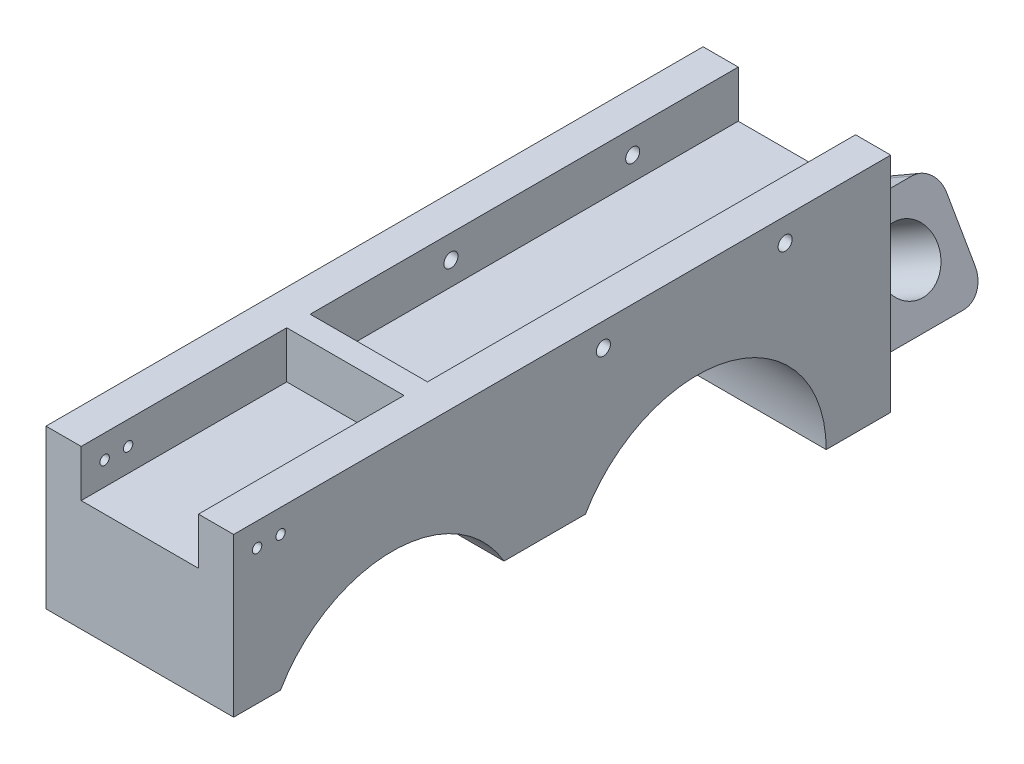
SolidWorks part; units mm, degrees
ref_plane "Спереди" through (0, 0, 0) normal (0, 0, 1) x (1, 0, 0)
ref_plane "Сверху" through (0, 0, 0) normal (0, 1, 0) x (1, 0, 0)
ref_plane "Справа" through (0, 0, 0) normal (1, 0, 0) x (0, 0, -1)
sketch "Эскиз1" plane through (0, 0, 0) normal (1, 0, 0) x (0, 0, -1)
  line L5 (0, 0) -> (0, -95)
  line L23 (-82.5, -95) -> (-130.1314, -67.5) construction
  line L24 (-27.5, -95) -> (0, -95)
  line L25 (-82.5, -95) -> (-27.5, -95) construction
  line L26 (-82.5, -95) -> (-82.5, -40) construction
  line L27 (-92.5, -40.9167) -> (-92.5, -50)
  line L28 (-92.5, -50) -> (-72.5, -50)
  line L29 (-72.5, -50) -> (-72.5, -40.9167)
  line L30 (-212.5, -95) -> (-212.5, 0) construction
  line L31 (-137.5, -95) -> (-157.5, -95) construction
  line L32 (-130.1314, -67.5) -> (-164.8686, -67.5)
  line L33 (-260.1314, -67.5) -> (-280.1314, -67.5)
  line L36 (0, 0) -> (-280.1314, 0)
  line L37 (-280.1314, 0) -> (-280.1314, -67.5)
  line L38 (-222.5, -40.9167) -> (-222.5, -50)
  line L39 (-222.5, -50) -> (-202.5, -50)
  line L40 (-202.5, -50) -> (-202.5, -40.9167)
  arc A6 (-130.1314, -67.5) -> (-92.5, -40.9167) centre (-82.5, -95) cw
  arc A7 (-72.5, -40.9167) -> (-27.5, -95) centre (-82.5, -95) cw
  arc A8 (-130.1314, -67.5) -> (-27.5, -95) centre (-82.5, -95) cw construction
  circle A12 centre (-45, -10) radius 3
  arc A13 (-27.5, -95) -> (-137.5, -95) centre (-82.5, -95) ccw construction
  arc A14 (-157.5, -95) -> (-202.5, -40.9167) centre (-212.5, -95) ccw construction
  arc A15 (-164.8686, -67.5) -> (-202.5, -40.9167) centre (-212.5, -95) ccw
  circle A16 centre (-122.5, -10) radius 3
  arc A17 (-222.5, -40.9167) -> (-267.5, -95) centre (-212.5, -95) ccw construction
  arc A18 (-222.5, -40.9167) -> (-260.1314, -67.5) centre (-212.5, -95) ccw
  circle A19 centre (-260.1314, -10) radius 2
  circle A20 centre (-270.1314, -10) radius 2
  point P0 (0, 0)
  dimension "D1" = 27.5
  dimension "D4" = 10
  dimension "D3" = 20
  dimension "D2" = 55
  dimension "D8" = 20
  dimension "D12" = 37.5
  dimension "D14" = 6
  dimension "D6" = 20
  dimension "D7" = 55
  dimension "D9" = 40
  dimension "D13" = 4
  dimension "D5" = 60
  dimension "D10" = 10
  dimension "D11" = 40
  dimension "D15" = 10
  dimension "D16" = 10
  dimension "D17" = 10
extrude "Бобышка-Вытянуть1" add sketch "Эскиз1" along normal blind 80
sketch "Эскиз3" plane through (0, 0, 0) normal (0, 0, -1) x (-1, 0, 0)
  line L0 (-80, -48.812) -> (0, -95) construction
  line L1 (-80, -95) -> (-80, 0) construction
  line L2 (-80, -95) -> (0, -95) construction
  dimension "D1" = 30
ref_plane "Плоскость1" through (41.1362, -71.25, 0) normal (-0.5, 0.866, 0) x (-0.866, -0.5, 0)
sketch "Эскиз4" plane through (0, -50, 0) normal (0, -1, 0) x (1, 0, 0)
  line L5 (80, 72.5) -> (0, 72.5) construction
  line L6 (0, 92.5) -> (15, 92.5)
  line L11 (0, 92.5) -> (0, 72.5)
  line L12 (0, 72.5) -> (15, 72.5)
  line L18 (15, 92.5) -> (15, 72.5)
  line L20 (80, 92.5) -> (65, 92.5)
  line L21 (80, 92.5) -> (80, 72.5)
  line L22 (80, 72.5) -> (65, 72.5)
  line L23 (65, 92.5) -> (65, 72.5)
  dimension "D1" = 15
extrude "Вырез-Вытянуть4" cut sketch "Эскиз4" against normal up to surface (9.0833 mm away)
sketch "Эскиз5" plane through (41.1362, -71.25, 0) normal (-0.5, 0.866, 0) x (-0.866, -0.5, 0)
  line L0 (-44.876, 0) -> (47.5, 0) construction
  line L1 (-27.5, 0) -> (47.5, 0)
  line L2 (-27.5, 0) -> (-27.5, -45)
  line L3 (-27.5, -45) -> (47.5, -45)
  line L4 (47.5, 0) -> (47.5, -45)
  dimension "D1" = 45
  dimension "D2" = 75
extrude "Бобышка-Вытянуть2" add sketch "Эскиз5" along normal mid plane 44.3
sketch "Эскиз6" plane through (23.8157, 13.75, 0) normal (0.866, 0.5, 0) x (0, 0, -1)
  line L0 (22.5, -60.1224) -> (22.5, -104.4224) construction
  line L1 (0, -60.1224) -> (45, -60.1224) construction
  line L2 (0, -104.4224) -> (45, -104.4224) construction
  line L3 (45, -82.2724) -> (0, -82.2724) construction
  line L4 (45, -60.1224) -> (45, -104.4224) construction
  line L5 (52.4823, -82.2724) -> (-52.4823, -82.2724) construction
  line L6 (0, -122.2724) -> (0, -40) construction
  circle A0 centre (22.5, -82.2724) radius 12.5
  dimension "D1" = 25
extrude "Вырез-Вытянуть5" cut sketch "Эскиз6" against normal blind 60
sketch "Эскиз7" plane through (-28.1458, -16.25, 0) normal (0.866, 0.5, 0) x (0, 0, -1)
  line L0 (22.5, -60.1224) -> (22.5, -104.4224) construction
  line L1 (0, -60.1224) -> (45, -60.1224) construction
  line L2 (0, -104.4224) -> (45, -104.4224) construction
  line L3 (0, -82.2724) -> (45, -82.2724) construction
  line L4 (0, -60.1224) -> (0, -104.4224) construction
  line L5 (45, -60.1224) -> (45, -104.4224) construction
  circle A0 centre (22.5, -82.2724) radius 3
  dimension "D1" = 6
extrude "Вырез-Вытянуть6" cut sketch "Эскиз7" against normal up to surface (15 mm away) up to face at (0, -95, -18)
fillet "Скругление1" radius 10 4 edges at (27.6875, -104.5912, 0) (-5.5375, -72.6205, 0) (21.401, -57.0675, -45) (43.551, -95.4325, -45)
sketch "Эскиз8" plane through (-41.1362, -23.75, 0) normal (-0.866, -0.5, 0) x (0, 0, 1)
  line L0 (-22.5, -104.4224) -> (-22.5, -60.1224) construction
  line L1 (-35, -104.4224) -> (-10, -104.4224) construction
  line L2 (-35, -60.1224) -> (-10, -60.1224) construction
  line L3 (52.4823, -82.2724) -> (-52.4823, -82.2724) construction
  circle A0 centre (-22.5, -73.7724) radius 1.5
  circle A1 centre (-14, -82.2724) radius 1.5
  circle A2 centre (-22.5, -90.7724) radius 1.5
  circle A3 centre (-31, -82.2724) radius 1.5
  point P10 (-22.5, -82.2724)
  point P20 (-22.5, -82.2724)
  dimension "D1" = 8.5
  dimension "D2" = 3
  dimension "D4" = 8.5
  dimension "D3" = 4
extrude "Вырез-Вытянуть7" cut sketch "Эскиз8" against normal up to surface (15 mm away) up to face at (11.4904, -84.9019, -22.5)
sketch "Эскиз9" plane through (0, -50, 0) normal (0, -1, 0) x (1, 0, 0)
  line L0 (80, 202.5) -> (0, 202.5) construction
  line L1 (0, 222.5) -> (15, 222.5)
  line L2 (0, 222.5) -> (0, 202.5)
  line L3 (0, 202.5) -> (15, 202.5)
  line L4 (15, 222.5) -> (15, 202.5)
  line L5 (80, 202.5) -> (0, 202.5) construction
  line L6 (80, 222.5) -> (65, 222.5)
  line L7 (80, 222.5) -> (80, 202.5)
  line L8 (80, 202.5) -> (65, 202.5)
  line L9 (65, 222.5) -> (65, 202.5)
  dimension "D1" = 15
extrude "Вырез-Вытянуть8" cut sketch "Эскиз9" against normal up to surface (9.0833 mm away)
sketch "Эскиз10" plane through (0, 0, 0) normal (0, 0, -1) x (-1, 0, 0)
  line L0 (-80, 0) -> (0, 0) construction
  line L1 (-65, -20) -> (-15, -20)
  line L2 (-65, -20) -> (-65, 0)
  line L3 (-65, 0) -> (-15, 0)
  line L4 (-15, -20) -> (-15, 0)
  line L5 (-65, -20) -> (-15, 0) construction
  line L6 (-65, 0) -> (-15, -20) construction
  line L7 (0, -69.4234) -> (0, 0) construction
  point P0 (-40, -10)
  point P7 (0, 0)
  dimension "D1" = 20
  dimension "D2" = 50
  dimension "D3" = 40
extrude "Вырез-Вытянуть9" cut sketch "Эскиз10" against normal up to surface (280.1314 mm away) up to face at (40, -33.75, 280.1314)
sketch "Эскиз11" plane through (0, -20, 0) normal (0, 1, 0) x (1, 0, 0)
  line L0 (15, -280.1314) -> (15, 0) construction
  line L1 (15, -192.5) -> (65, -192.5)
  line L2 (15, -192.5) -> (15, -182.5)
  line L3 (15, -182.5) -> (65, -182.5)
  line L4 (65, -192.5) -> (65, -182.5)
  line L5 (65, -280.1314) -> (65, 0) construction
  line L6 (15, -72.5) -> (15, -92.5) construction
  point P10 (15, -82.5)
  dimension "D1" = 100
  dimension "D2" = 10
extrude "Бобышка-Вытянуть3" add sketch "Эскиз11" along normal up to surface (20 mm away) up to face at (7.5, 0, 140.0657)
